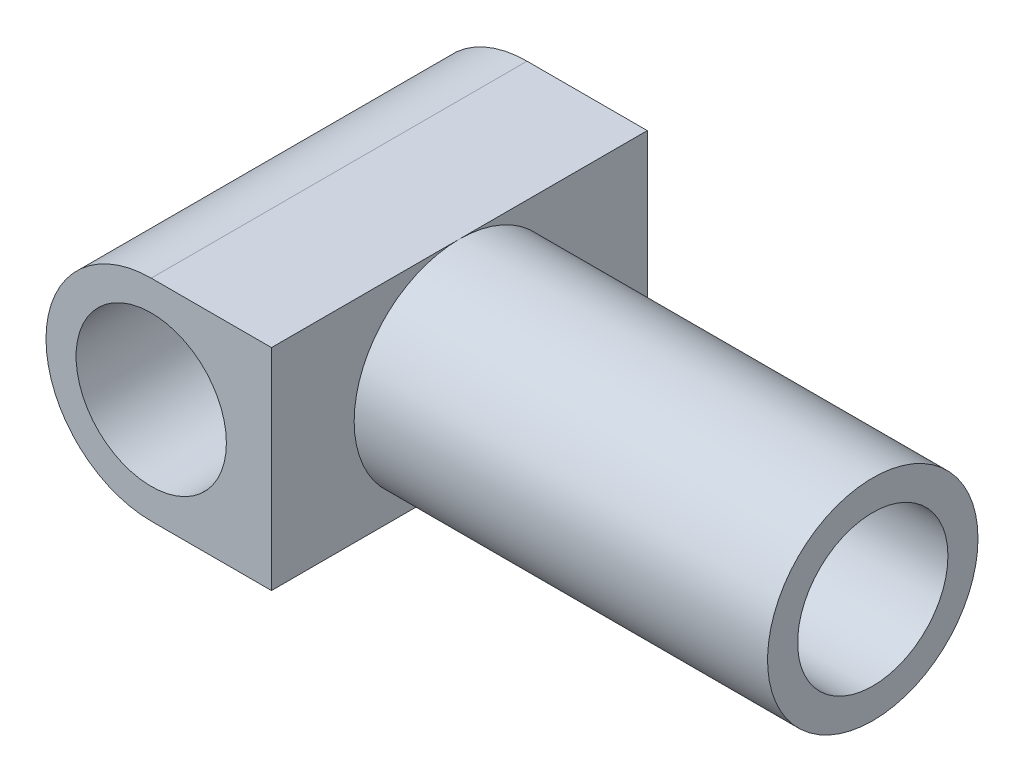
SolidWorks part; units mm, degrees
material "ABS"
ref_plane "Płaszczyzna przednia" through (0, 0, 0) normal (0, 0, 1) x (1, 0, 0)
ref_plane "Płaszczyzna górna" through (0, 0, 0) normal (0, 1, 0) x (1, 0, 0)
ref_plane "Płaszczyzna prawa" through (0, 0, 0) normal (1, 0, 0) x (0, 0, -1)
sketch "Szkic1" plane through (0, 0, 0) normal (0, 0, 1) x (1, 0, 0)
  line L0 (0, 7) -> (8, 7)
  line L1 (8, 7) -> (8, -7)
  line L2 (8, -7) -> (0, -7)
  circle A0 centre (0, 0) radius 5
  arc A1 (0, 7) -> (0, -7) centre (0, 0) ccw
  dimension "D1" = 14
  dimension "D2" = 10
  dimension "D3" = 8
extrude "Dodanie-wyciągnięcie1" add sketch "Szkic1" along normal blind 25
sketch "Szkic2" plane through (8, 0, 0) normal (1, 0, 0) x (0, 0, -1)
  circle A0 centre (-12.5, 0) radius 5
  circle A1 centre (-12.5, 0) radius 7
  dimension "D1" = 14
  dimension "D2" = 10
extrude "Dodanie-wyciągnięcie2" add sketch "Szkic2" along normal blind 27.5
